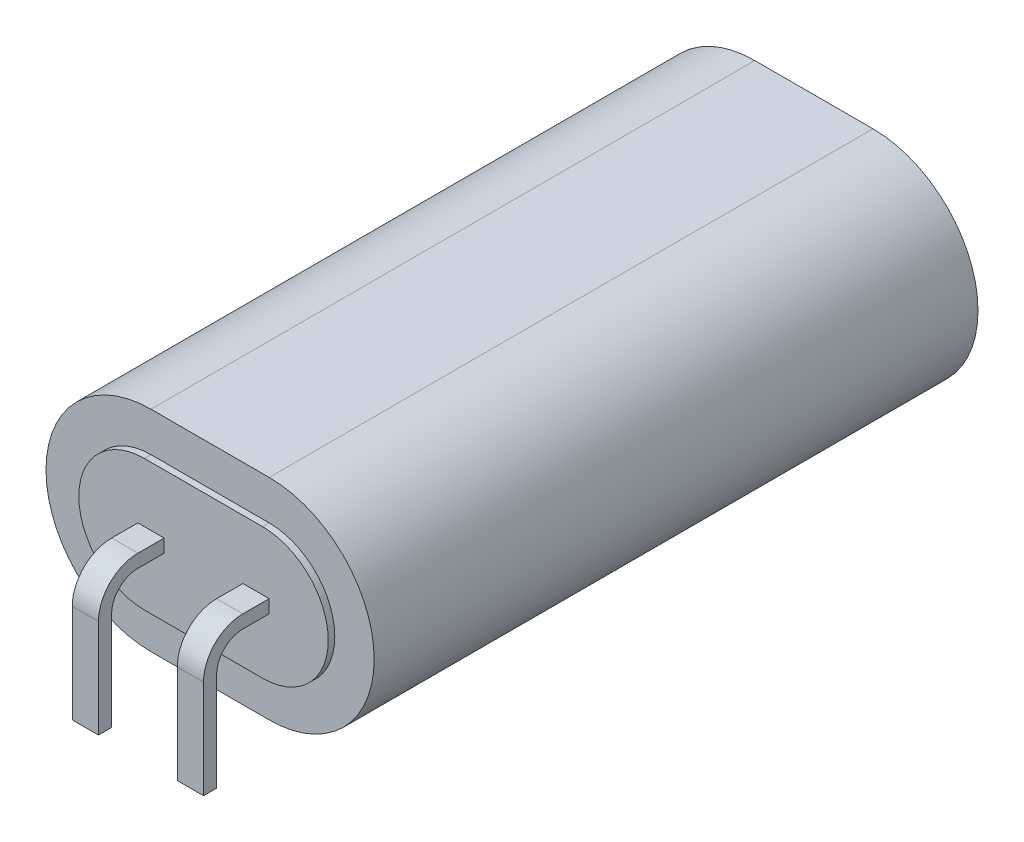
SolidWorks part; units mm, degrees
material "Copper"
ref_plane "Front Plane" through (0, 0, 0) normal (0, 0, 1) x (1, 0, 0)
ref_plane "Top Plane" through (0, 0, 0) normal (0, 1, 0) x (1, 0, 0)
ref_plane "Right Plane" through (0, 0, 0) normal (1, 0, 0) x (0, 0, -1)
other "Configuration Table"
sketch "Sketch1" plane through (0, 0, 0) normal (0, 0, 1) x (1, 0, 0)
  line L0 (4.5, 8) -> (-4.5, -8) construction
  line L1 (-4.5, 8) -> (4.5, 8)
  line L3 (-4.5, -8) -> (4.5, -8)
  arc A0 (4.5, 8) -> (4.5, -8) centre (4.5, 0) cw
  arc A1 (-4.5, 8) -> (-4.5, -8) centre (-4.5, 0) ccw
  point P4 (0, 0)
  dimension "D2" = 25
  dimension "D1" = 16
extrude "Extrude1" add sketch "Sketch1" along normal mid plane 46
sketch "Sketch2" plane through (0, 0, 0) normal (0, 0, 1) x (1, 0, 0)
  line L4 (-4.5, -5) -> (4.5, -5)
  line L5 (4.5, 5) -> (-4.5, 5)
  line L6 (-4.5, -5) -> (4.5, -5)
  line L7 (4.5, 5) -> (-4.5, 5)
  arc A4 (-4.5, 5) -> (-4.5, -5) centre (-4.5, 0) ccw
  arc A5 (4.5, -5) -> (4.5, 5) centre (4.5, 0) ccw
  arc A6 (-4.5, 5) -> (-4.5, -5) centre (-4.5, 0) ccw
  arc A7 (4.5, -5) -> (4.5, 5) centre (4.5, 0) ccw
  dimension "D1" = 3
extrude "Extrude2" add sketch "Sketch2" along normal mid plane 47
ref_plane "Plane1" through (-4, 0, 0) normal (1, 0, 0) x (0, 0, -1)
sketch "Sketch3" plane through (-4, 0, 0) normal (1, 0, 0) x (0, 0, -1)
  line L0 (0, 0) -> (-25.5, 0)
  line L1 (-28, -2.5) -> (-28, -10)
  line L3 (-23, -8) -> (23, -8) construction
  line L4 (-36.2881, -8) -> (23, -8) construction
  line L6 (-23, 8) -> (-23, -8) construction
  arc A0 (-25.5, 0) -> (-28, -2.5) centre (-25.5, -2.5) ccw
  dimension "D2" = 2.5
  dimension "D1" = 5
  dimension "D3" = 2
sketch "Sketch6" plane through (0, 0, 0) normal (0, 0, 1) x (1, 0, 0)
  line L0 (-5, 0.5) -> (-3, -0.5) construction
  line L1 (-5, 0.5) -> (-3, 0.5)
  line L2 (-5, 0.5) -> (-5, -0.5)
  line L3 (-5, -0.5) -> (-3, -0.5)
  line L4 (-3, 0.5) -> (-3, -0.5)
  point P7 (-4, 0)
  dimension "D1" = 2
  dimension "D2" = 1
sweep "Sweep1" add profiles "Sketch6" path "Sketch3"
mirror "Mirror1" about plane through (0, 0, 0) normal (1, 0, 0) of "Sweep1"
mirror "Mirror2" about plane through (0, 0, 0) normal (0, 0, 1) of "Sweep1", "Mirror1"
sketch "Sketch7" plane through (0, 8, 0) normal (0, 1, 0) x (1, 0, 0)
  line L0 (-2.8693, 19.72) -> (-2.8693, -19.72) construction
  line L1 (-2.8693, 0) -> (0, 0) construction
  text T0 "2 W MAX LOAD" font "Century Gothic" height in points 12
extrude "Cut-Extrude1" [suppressed] cut sketch "Sketch7" against normal blind 0.5
